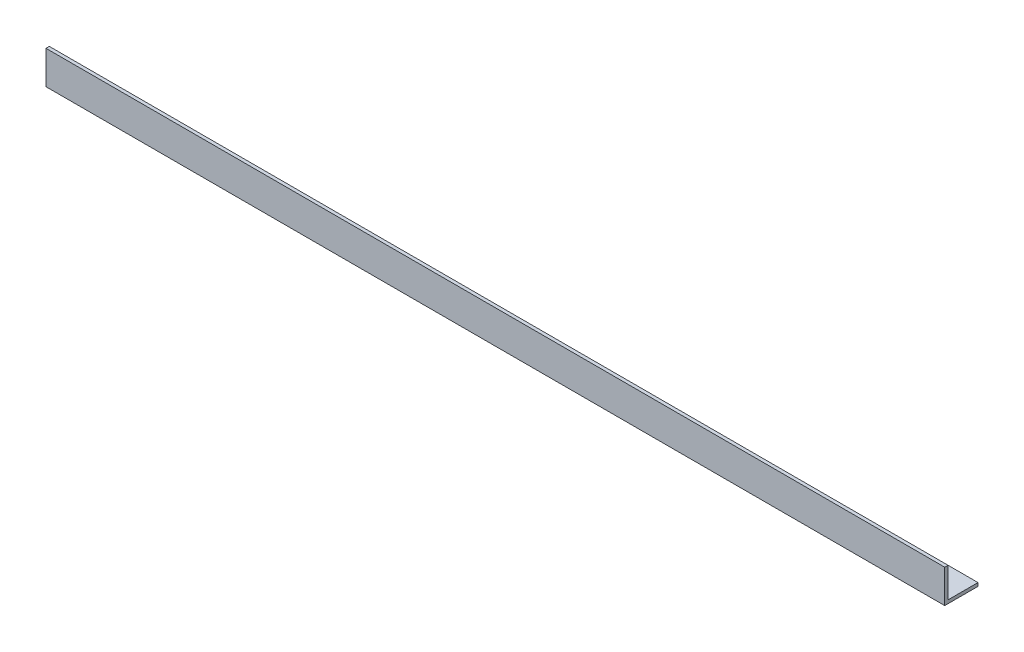
SolidWorks part; units mm, degrees
material "1060 Сплав"
ref_plane "Спереди" through (0, 0, 0) normal (0, 0, 1) x (1, 0, 0)
ref_plane "Сверху" through (0, 0, 0) normal (0, 1, 0) x (1, 0, 0)
ref_plane "Справа" through (0, 0, 0) normal (1, 0, 0) x (0, 0, -1)
sketch "Эскиз1" plane through (0, 0, 0) normal (1, 0, 0) x (0, 0, -1)
  line L1 (-5, 5) -> (-4, 5)
  line L2 (-5, 5) -> (-5, -5)
  line L3 (-5, -5) -> (5, -5)
  line L4 (5, -4) -> (5, -5)
  line L5 (-5, 5) -> (5, -5) construction
  line L6 (-5, -5) -> (5, 5) construction
  line L7 (5, 5) -> (-4, 5) construction
  line L8 (5, 5) -> (5, -4) construction
  line L9 (5, -4) -> (-4, -4)
  line L10 (-4, 5) -> (-4, -4)
  point P0 (0, 0)
  dimension "D1" = 10
  dimension "D2" = 1
extrude "Бобышка-Вытянуть1" add sketch "Эскиз1" along normal blind 270
sketch "Эскиз2" plane through (0, -4, 0) normal (0, 1, 0) x (1, 0, 0)
  line L0 (135, 5) -> (135, -4) construction
  line L1 (270, 5) -> (0, 5) construction
  line L2 (270, -4) -> (0, -4) construction
  line L3 (135, 0.5) -> (72.5, 0.5) construction
  line L5 (72.5, 0.5) -> (10, 0.5) construction
  circle A0 centre (135, 0.5) radius 1.5
  circle A1 centre (72.5, 0.5) radius 1.5
  circle A2 centre (10, 0.5) radius 1.5
  circle A3 centre (260, 0.5) radius 1.5
  circle A4 centre (197.5, 0.5) radius 1.5
  dimension "D1" = 3
  dimension "D2" = 62.5
extrude "Вырез-Вытянуть1" cut sketch "Эскиз2" against normal up to surface (1 mm away) up to face at (135, -5, 0)
